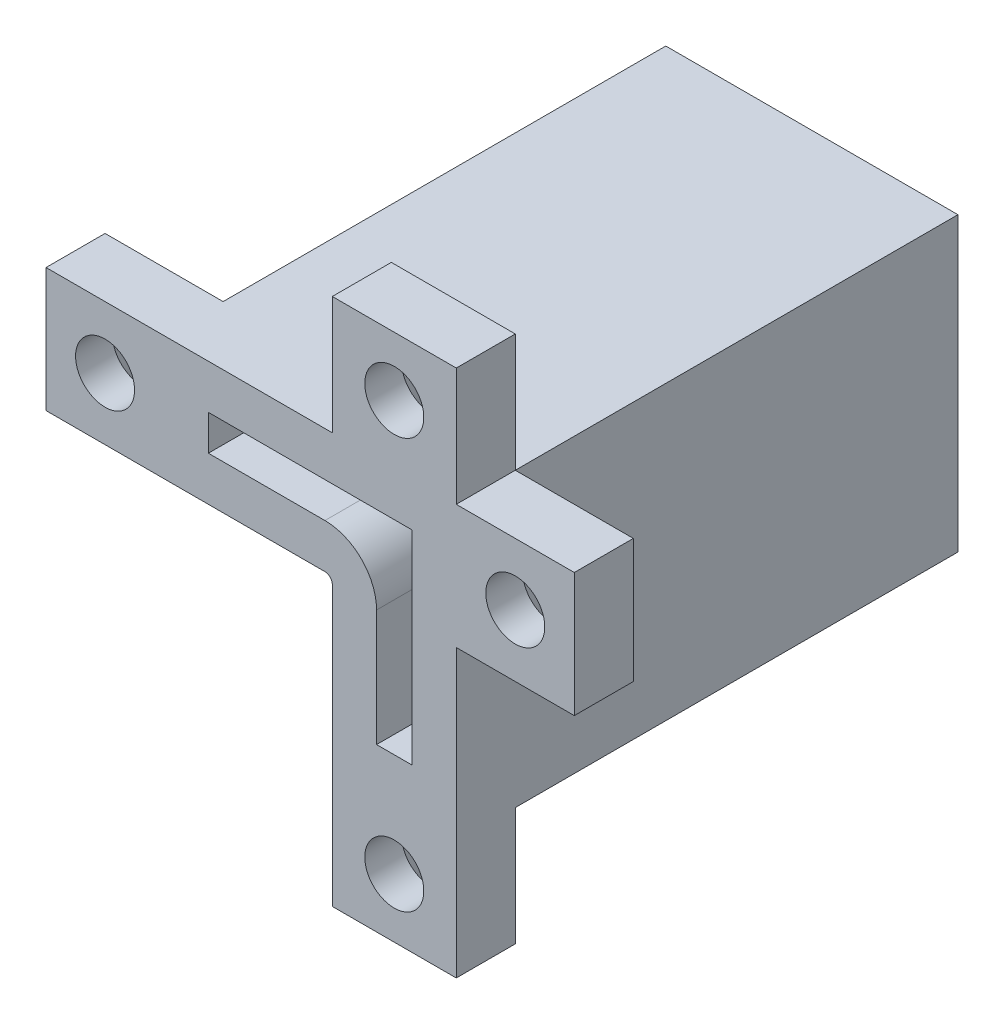
SolidWorks part; units mm, degrees
ref_plane "Front Plane" through (0, 0, 0) normal (0, 0, 1) x (1, 0, 0)
ref_plane "Top Plane" through (0, 0, 0) normal (0, 1, 0) x (1, 0, 0)
ref_plane "Right Plane" through (0, 0, 0) normal (1, 0, 0) x (0, 0, -1)
ref_plane "Plane1" through (0, 0, 10) normal (0, 0, 1) x (1, 0, 0)
sketch "Sketch2" plane through (0, 0, 10) normal (0, 0, 1) x (1, 0, 0)
  line L6 (-17.9441, 79.3281) -> (-17.9441, 65.5281)
  line L7 (-17.9441, 65.5281) -> (-20.3441, 65.5281)
  line L8 (-20.3441, 65.5281) -> (-20.3441, 73.4281)
  line L9 (-23.8441, 76.9281) -> (-31.7441, 76.9281)
  line L10 (-31.7441, 76.9281) -> (-31.7441, 79.3281)
  line L11 (-31.7441, 79.3281) -> (-17.9441, 79.3281)
  line L12 (-14.9441, 82.3281) -> (-14.9441, 62.5281)
  line L13 (-14.9441, 62.5281) -> (-23.3441, 62.5281)
  line L14 (-23.3441, 62.5281) -> (-23.3441, 73.4281)
  line L15 (-23.8441, 73.9281) -> (-34.7441, 73.9281)
  line L16 (-34.7441, 73.9281) -> (-34.7441, 82.3281)
  line L17 (-34.7441, 82.3281) -> (-14.9441, 82.3281)
  arc A1 (-20.3441, 73.4281) -> (-23.8441, 76.9281) centre (-23.8441, 73.4281) ccw
  arc A2 (-23.3441, 73.4281) -> (-23.8441, 73.9281) centre (-23.8441, 73.4281) ccw
  dimension "D1" = 3
extrude "Boss-Extrude1" add sketch "Sketch2" along normal blind 30
sketch "Sketch3" plane through (0, 0, 40) normal (0, 0, 1) x (1, 0, 0)
  line L6 (-23.3441, 62.5281) -> (-14.9441, 62.5281) construction
  line L7 (-34.7441, 82.3281) -> (-42.7441, 82.3281)
  line L9 (-34.7441, 73.9281) -> (-42.7441, 73.9281)
  line L10 (-42.7441, 82.3281) -> (-42.7441, 73.9281)
  line L12 (-23.3441, 62.5281) -> (-23.3441, 54.5281)
  line L13 (-23.3441, 54.5281) -> (-14.9441, 54.5281)
  line L14 (-14.9441, 62.5281) -> (-14.9441, 54.5281)
  line L15 (-14.9441, 82.3281) -> (-34.7441, 82.3281) construction
  line L17 (-23.3441, 82.3281) -> (-23.3441, 90.3281)
  line L18 (-23.3441, 90.3281) -> (-14.9441, 90.3281)
  line L19 (-14.9441, 82.3281) -> (-14.9441, 90.3281)
  line L20 (-14.9441, 62.5281) -> (-14.9441, 82.3281) construction
  line L21 (-14.9441, 82.3281) -> (-6.9441, 82.3281)
  line L23 (-14.9441, 73.9281) -> (-6.9441, 73.9281)
  line L24 (-6.9441, 82.3281) -> (-6.9441, 73.9281)
  line L25 (-31.7441, 76.9281) -> (-23.8441, 76.9281) construction
  line L26 (-20.3441, 73.4281) -> (-20.3441, 65.5281) construction
  line L27 (-20.3441, 65.5281) -> (-17.9441, 65.5281) construction
  line L28 (-17.9441, 65.5281) -> (-17.9441, 79.3281) construction
  line L29 (-17.9441, 79.3281) -> (-31.7441, 79.3281) construction
  line L30 (-31.7441, 79.3281) -> (-31.7441, 76.9281) construction
  line L31 (-14.9441, 82.3281) -> (-34.7441, 82.3281)
  line L32 (-34.7441, 82.3281) -> (-34.7441, 73.9281)
  line L33 (-34.7441, 73.9281) -> (-23.8441, 73.9281)
  line L34 (-23.3441, 73.4281) -> (-23.3441, 62.5281)
  line L35 (-23.3441, 62.5281) -> (-14.9441, 62.5281)
  line L36 (-14.9441, 62.5281) -> (-14.9441, 82.3281)
  line L37 (-23.3441, 82.3281) -> (-34.7441, 82.3281)
  line L38 (-31.7441, 76.9281) -> (-23.8441, 76.9281)
  line L39 (-34.7441, 73.9281) -> (-23.8441, 73.9281)
  line L40 (-23.3441, 73.4281) -> (-23.3441, 62.5281)
  line L41 (-20.3441, 73.4281) -> (-20.3441, 65.5281)
  line L42 (-14.9441, 62.5281) -> (-14.9441, 73.9281)
  line L43 (-20.3441, 65.5281) -> (-17.9441, 65.5281)
  line L44 (-17.9441, 65.5281) -> (-17.9441, 79.3281)
  line L45 (-17.9441, 79.3281) -> (-31.7441, 79.3281)
  line L46 (-31.7441, 79.3281) -> (-31.7441, 76.9281)
  arc A1 (-20.3441, 73.4281) -> (-23.8441, 76.9281) centre (-23.8441, 73.4281) ccw construction
  arc A2 (-23.3441, 73.4281) -> (-23.8441, 73.9281) centre (-23.8441, 73.4281) ccw
  arc A3 (-23.3441, 73.4281) -> (-23.8441, 73.9281) centre (-23.8441, 73.4281) ccw
  arc A4 (-20.3441, 73.4281) -> (-23.8441, 76.9281) centre (-23.8441, 73.4281) ccw
  point P13 (0, 0)
  point P22 (0, 0)
  point P24 (0, 0)
  point P26 (0, 0)
  point P28 (0, 0)
  point P29 (0, 0)
  dimension "D1" = 8.4
  dimension "D2" = 8.4
  dimension "D3" = 8
  dimension "D4" = 8
  dimension "D5" = 8
  dimension "D6" = 8
  dimension "D7" = 0
extrude "Boss-Extrude2" add sketch "Sketch3" along normal blind 4
sketch "Sketch4" plane through (0, 0, 40) normal (0, 0, -1) x (-1, 0, 0)
  line L0 (23.3441, 86.3281) -> (14.9441, 86.3281) construction
  line L1 (23.3441, 90.3281) -> (23.3441, 82.3281) construction
  line L2 (14.9441, 82.3281) -> (14.9441, 90.3281) construction
  line L3 (10.9441, 82.3281) -> (10.9441, 73.9281) construction
  line L4 (6.9441, 82.3281) -> (14.9441, 82.3281) construction
  line L5 (14.9441, 73.9281) -> (6.9441, 73.9281) construction
  line L6 (38.7441, 82.3281) -> (38.7441, 73.9281) construction
  line L7 (23.3441, 82.3281) -> (42.7441, 82.3281) construction
  line L8 (42.7441, 73.9281) -> (23.8441, 73.9281) construction
  line L9 (23.3441, 58.5281) -> (14.9441, 58.5281) construction
  line L10 (23.3441, 73.4281) -> (23.3441, 54.5281) construction
  line L11 (14.9441, 54.5281) -> (14.9441, 73.9281) construction
  line L13 (42.7441, 82.3281) -> (42.7441, 73.9281) construction
  line L14 (23.3441, 54.5281) -> (14.9441, 54.5281) construction
  circle A0 centre (19.1441, 86.3281) radius 2
  circle A1 centre (10.9441, 78.1281) radius 2
  circle A2 centre (38.7441, 78.1281) radius 2
  circle A3 centre (19.1441, 58.5281) radius 2
  dimension "D3" = 4
  dimension "D4" = 4
  dimension "D5" = 4
  dimension "D6" = 4
  dimension "D1" = 4
  dimension "D2" = 4
extrude "Cut-Extrude1" cut sketch "Sketch4" against normal up to surface (4 mm away) up to face at (-21.2515, 76.0207, 44)
chamfer "Chamfer1" distance 1.5 angle 45 4 edges at (-21.1441, 86.3281, 40) (-12.9441, 78.1281, 40) (-21.1441, 58.5281, 40) (-40.7441, 78.1281, 40)
